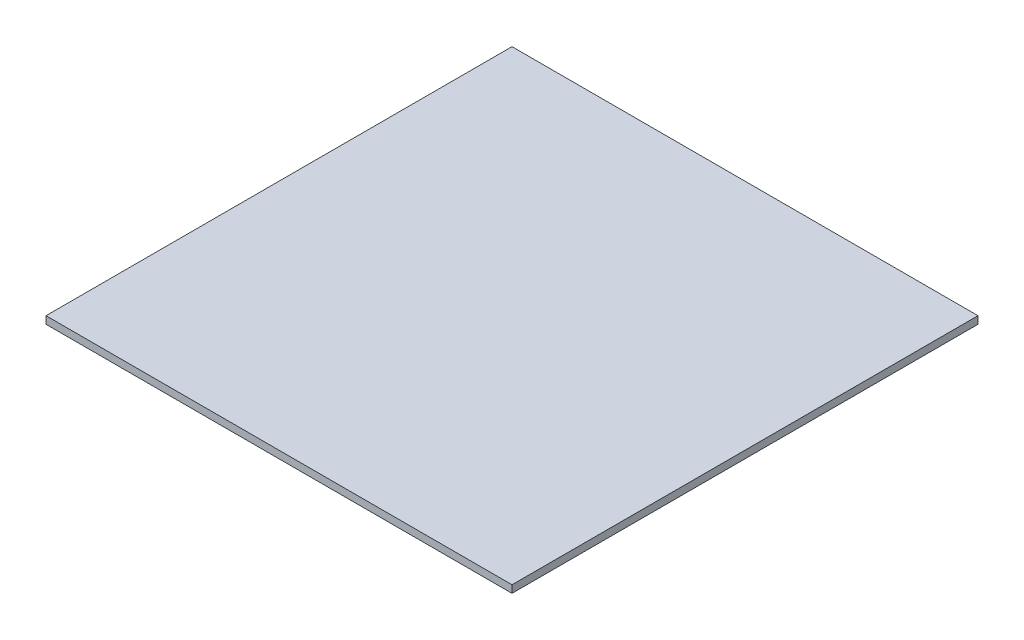
SolidWorks part; units mm, degrees
ref_plane "Front Plane" through (0, 0, 0) normal (0, 0, 1) x (1, 0, 0)
ref_plane "Top Plane" through (0, 0, 0) normal (0, 1, 0) x (1, 0, 0)
ref_plane "Right Plane" through (0, 0, 0) normal (1, 0, 0) x (0, 0, -1)
sketch "Sketch1" plane through (0, 0, 0) normal (0, 1, 0) x (1, 0, 0)
  line L1 (-50, -50) -> (50, -50)
  line L2 (-50, -50) -> (-50, 50)
  line L3 (-50, 50) -> (50, 50)
  line L4 (50, -50) -> (50, 50)
  line L5 (-50, -50) -> (50, 50) construction
  line L6 (-50, 50) -> (50, -50) construction
  point P0 (0, 0)
  dimension "D1" = 100
  dimension "D2" = 100
extrude "Boss-Extrude1" add sketch "Sketch1" along normal blind 1.6
